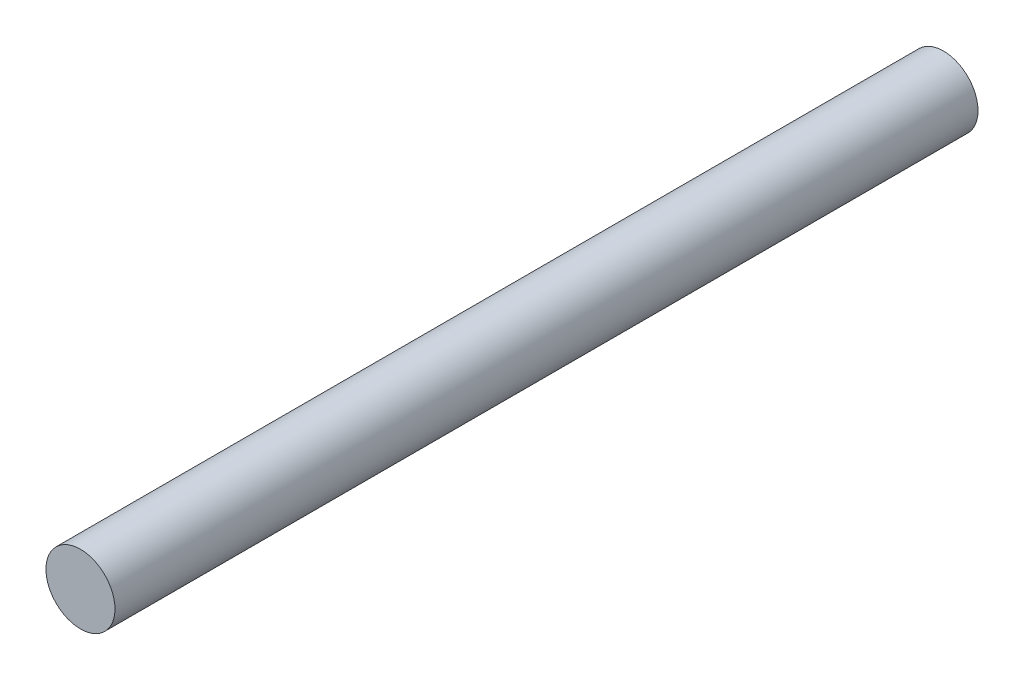
SolidWorks part; units mm, degrees
ref_plane "Front Plane" through (0, 0, 0) normal (0, 0, 1) x (1, 0, 0)
ref_plane "Top Plane" through (0, 0, 0) normal (0, 1, 0) x (1, 0, 0)
ref_plane "Right Plane" through (0, 0, 0) normal (1, 0, 0) x (0, 0, -1)
sketch "Sketch1" plane through (0, 0, 0) normal (0, 0, 1) x (1, 0, 0)
  circle A0 centre (-0.43, 0.4872) radius 0.4
  dimension "D1" = 0.8
extrude "Boss-Extrude1" add sketch "Sketch1" along normal blind 10
